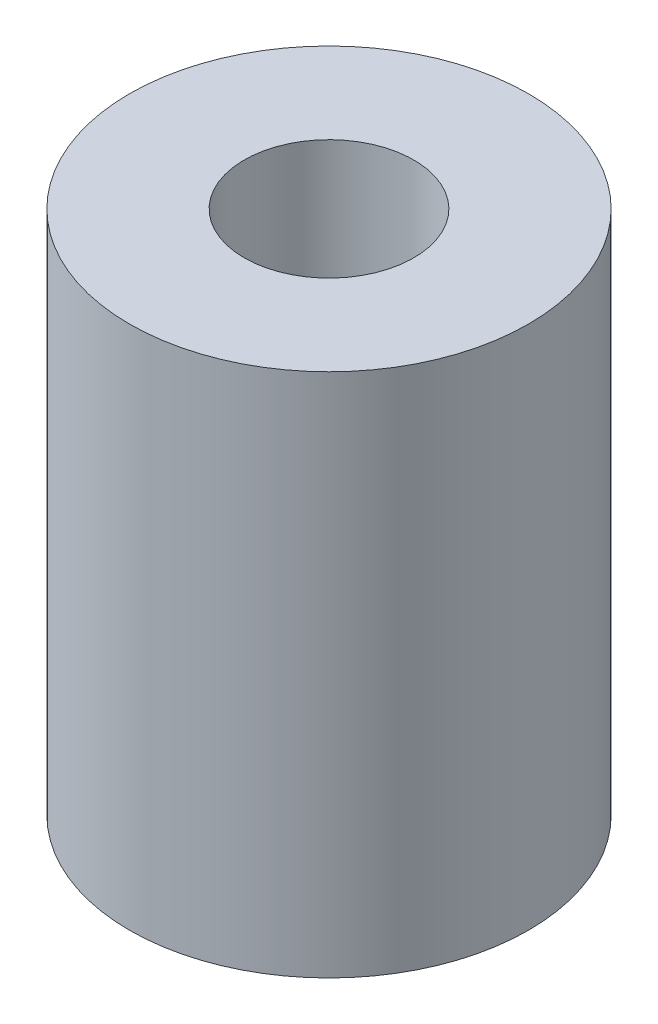
SolidWorks part; units mm, degrees
ref_plane "Front Plane" through (0, 0, 0) normal (0, 0, 1) x (1, 0, 0)
ref_plane "Top Plane" through (0, 0, 0) normal (0, 1, 0) x (1, 0, 0)
ref_plane "Right Plane" through (0, 0, 0) normal (1, 0, 0) x (0, 0, -1)
sketch "Sketch1" plane through (0, 0, 0) normal (0, 1, 0) x (1, 0, 0)
  circle A0 centre (0, 0) radius 9.4107
  circle A1 centre (0, 0) radius 2.5
  dimension "D1" = 18.8214
  dimension "D2" = 5
extrude "Boss-Extrude1" add sketch "Sketch1" along normal blind 24.765
sketch "Sketch2" plane through (0, 24.765, 0) normal (0, 1, 0) x (1, 0, 0)
  circle A0 centre (0, 0) radius 4
  dimension "D1" = 8
extrude "Cut-Extrude1" cut sketch "Sketch2" against normal blind 12.7
